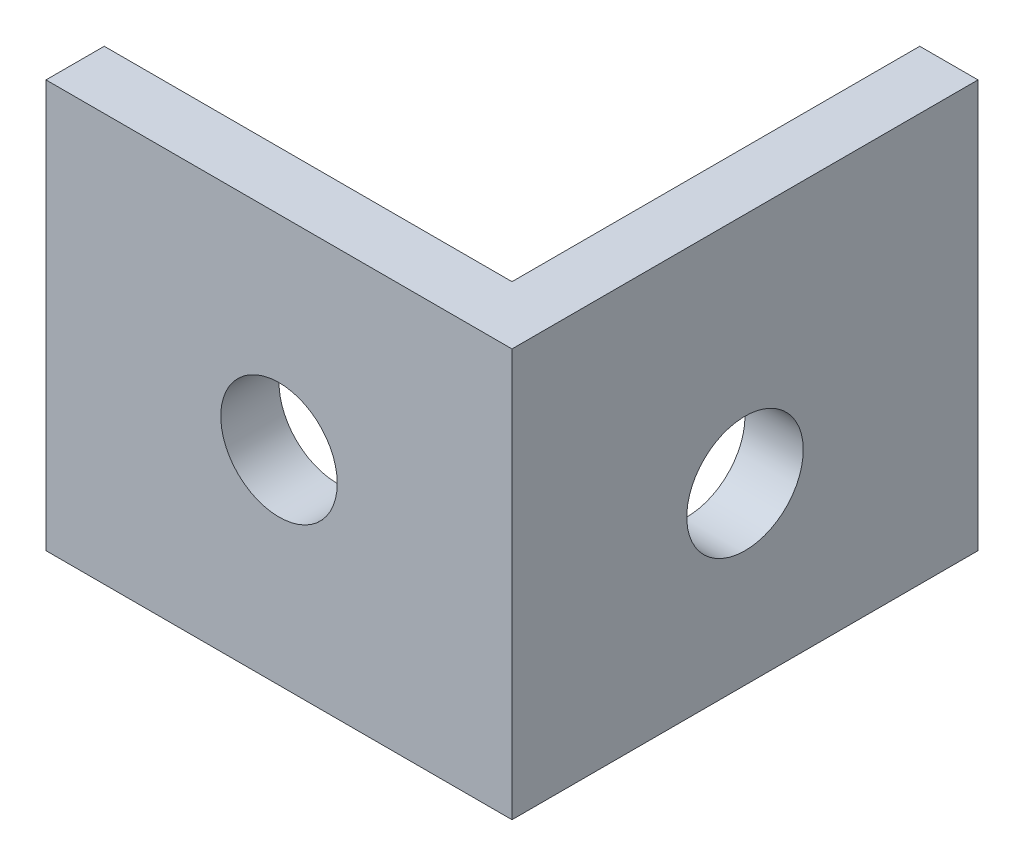
SolidWorks part; units mm, degrees
ref_plane "Front Plane" through (0, 0, 0) normal (0, 0, 1) x (1, 0, 0)
ref_plane "Top Plane" through (0, 0, 0) normal (0, 1, 0) x (1, 0, 0)
ref_plane "Right Plane" through (0, 0, 0) normal (1, 0, 0) x (0, 0, -1)
sketch "Sketch1" plane through (0, 0, 0) normal (0, 1, 0) x (1, 0, 0)
  line L0 (0, 0) -> (25.4, 0)
  line L1 (25.4, 0) -> (25.4, 25.4)
  line L2 (25.4, 25.4) -> (22.225, 25.4)
  line L3 (22.225, 25.4) -> (22.225, 3.175)
  line L4 (22.225, 3.175) -> (0, 3.175)
  line L5 (0, 3.175) -> (0, 0)
  dimension "D1" = 3.175
  dimension "D2" = 3.175
  dimension "D3" = 25.4
  dimension "D4" = 25.4
extrude "Boss-Extrude1" add sketch "Sketch1" along normal blind 22.225
sketch "Sketch2" plane through (25.4, 0, 0) normal (1, 0, 0) x (0, 0, -1)
  line L2 (0, 22.225) -> (0, 0) construction
  line L3 (25.4, 0) -> (3.175, 0) construction
  circle A0 centre (12.7, 9.525) radius 3.175
  dimension "D3" = 6.35
  dimension "D2" = 9.525
  dimension "D1" = 12.7
extrude "Cut-Extrude1" cut sketch "Sketch2" against normal blind 25.4
sketch "Sketch3" plane through (0, 0, 0) normal (0, 0, 1) x (1, 0, 0)
  line L0 (0, 22.225) -> (0, 0) construction
  line L1 (0, 0) -> (25.4, 0) construction
  circle A0 centre (12.7, 11.1125) radius 3.175
  dimension "D3" = 6.35
  dimension "D1" = 12.7
  dimension "D2" = 11.1125
extrude "Cut-Extrude2" cut sketch "Sketch3" against normal blind 25.4
